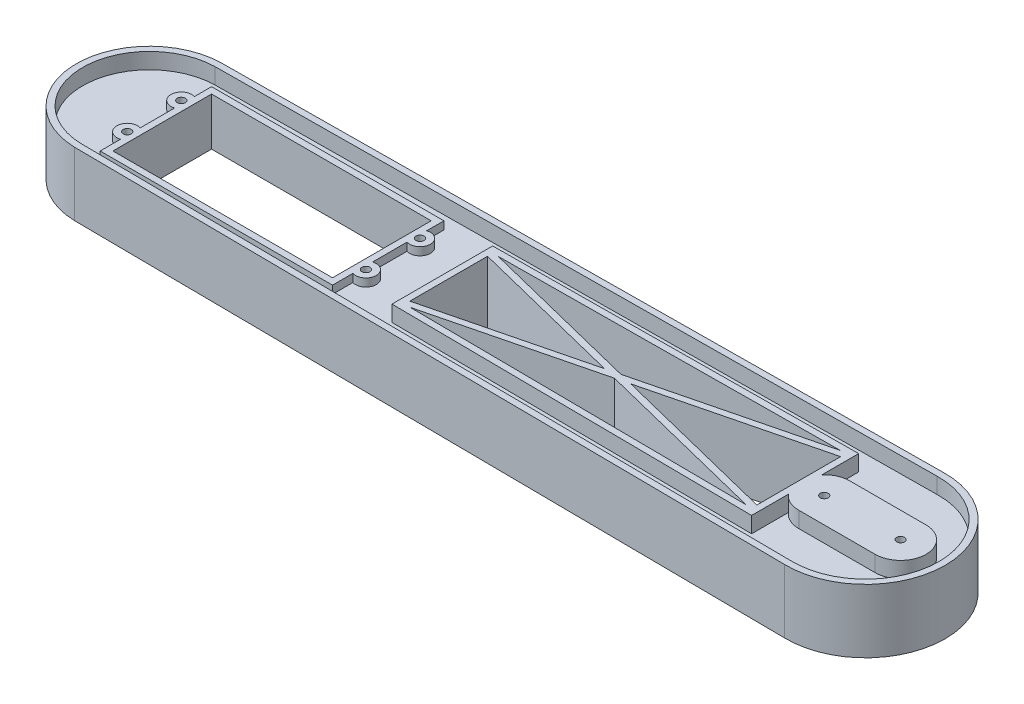
SolidWorks part; units mm, degrees
material "PET"
ref_plane "Front Plane" through (0, 0, 0) normal (0, 0, 1) x (1, 0, 0)
ref_plane "Top Plane" through (0, 0, 0) normal (0, 1, 0) x (1, 0, 0)
ref_plane "Right Plane" through (0, 0, 0) normal (1, 0, 0) x (0, 0, -1)
sketch "Sketch1" plane through (0, 0, 0) normal (0, 1, 0) x (1, 0, 0)
  line L0 (-0.4444, 19.9951) -> (0, 0) construction
  line L1 (-0.4444, 19.9951) -> (224.4444, 24.9938)
  line L2 (-55, 0) -> (55, 0) construction
  line L3 (-0.4444, -19.9951) -> (224.4444, -24.9938)
  line L4 (0, 0) -> (4, 0) construction
  line L5 (4, 0) -> (4, 15.5)
  line L6 (4, 15.5) -> (4, 0)
  line L7 (4, 15.5) -> (4, -15.5)
  line L8 (4, 15.5) -> (73, 15.5)
  line L9 (73, 15.5) -> (73, -15.5)
  line L10 (73, -15.5) -> (4, -15.5)
  line L11 (4, 15.5) -> (4, 9)
  line L12 (4, 9) -> (1, 9) construction
  line L13 (4, 0) -> (94, 0) construction
  line L14 (-0.2222, 9.9975) -> (224.6667, 14.9963) construction
  line L15 (-0.2222, -9.9975) -> (224.6667, -14.9963) construction
  line L16 (94, 0) -> (94, 12.0919)
  line L17 (94, 12.0919) -> (94, -12.0919)
  line L18 (94, 0) -> (204, 0) construction
  line L19 (204, 0) -> (204, 14.5369)
  line L20 (204, 14.5369) -> (204, -14.5369)
  line L21 (94, 12.0919) -> (204, 14.5369)
  line L22 (94, -12.0919) -> (204, -14.5369)
  line L23 (204, 0) -> (212, 0) construction
  line L24 (212, 0) -> (236, 0) construction
  arc A0 (224.4444, -24.9938) -> (224.4444, 24.9938) centre (225, 0) ccw
  arc A1 (-0.4444, 19.9951) -> (-0.4444, -19.9951) centre (0, 0) ccw
  circle A2 centre (1, 9) radius 1.25
  circle A3 centre (76, 9) radius 1.25
  circle A4 centre (76, -8) radius 1.25
  circle A5 centre (1, -8) radius 1.25
  arc A6 (224.6667, -14.9963) -> (224.6667, 14.9963) centre (225, 0) ccw construction
  arc A7 (-0.2222, 9.9975) -> (-0.2222, -9.9975) centre (0, 0) ccw construction
  circle A8 centre (212, 0) radius 1.25
  circle A9 centre (236, 0) radius 1.25
  dimension "D2" = 50
  dimension "D3" = 40
  dimension "D10" = 2.5
  dimension "D18" = 2.5
  dimension "D19" = 2.5
  dimension "D1" = 225
  dimension "D4" = 4
  dimension "D5" = 15.5
  dimension "D6" = 31
  dimension "D7" = 69
  dimension "D8" = 6.5
  dimension "D9" = 3
  dimension "D13" = 90
  dimension "D15" = 110
  dimension "D16" = 24
  dimension "D17" = 8
  dimension "D14" = 10
  dimension "D11" = 2
  dimension "D12" = 2
extrude "Boss-Extrude2" add sketch "Sketch1" along normal blind 10 contours L1 A1 L3 A0 A9 A8 A5 A4 A3 A2 L9 L10 L7 L5 L8 L22 L17 L16 L21 L19 L20
sketch "Sketch3" plane through (0, 10, 0) normal (0, 1, 0) x (1, 0, 0)
  line L1 (-0.5111, -22.9943) -> (224.4444, -24.9938)
  line L2 (224.4444, 24.9938) -> (-0.5111, 22.9943)
  arc A1 (-0.5111, 22.9943) -> (-0.5111, -22.9943) centre (0, 0) ccw
  arc A2 (224.4444, -24.9938) -> (224.4444, 24.9938) centre (225, 0) ccw construction
  arc A3 (224.4444, -24.9938) -> (224.4444, 24.9938) centre (225, 0) ccw
  dimension "D1" = 224.9556
  dimension "D2" = 224.9556
sketch "Sketch4" plane through (0, 10, 0) normal (0, 1, 0) x (1, 0, 0)
  line L0 (73, -15.5) -> (4, -15.5) construction
  line L1 (73, 15.5) -> (73, -15.5) construction
  line L2 (4, 15.5) -> (73, 15.5) construction
  line L3 (4, 15.5) -> (4, -15.5) construction
  line L4 (73, -15.5) -> (4, -15.5)
  line L5 (73, 15.5) -> (73, -15.5)
  line L6 (4, 15.5) -> (73, 15.5)
  line L7 (4, 15.5) -> (4, -15.5)
  line L11 (204, -14.5369) -> (204, 14.5369) construction
  line L12 (204, -14.8117) -> (204, 14.8117)
  line L14 (94, 13.834) -> (94, -13.834)
  line L16 (94, 12.0919) -> (94, -12.0919) construction
  line L17 (224.4444, 24.9938) -> (-0.5111, 22.9943) construction
  line L18 (94, 13.834) -> (204, 14.8117)
  line L19 (94, -13.834) -> (204, -14.8117)
  line L21 (-0.5111, -22.9943) -> (224.4444, -24.9938) construction
  circle A0 centre (1, 9) radius 1.25 construction
  circle A1 centre (1, -8) radius 1.25 construction
  circle A2 centre (1, 9) radius 1.25
  circle A3 centre (1, -8) radius 1.25
  circle A4 centre (76, 9) radius 1.25 construction
  circle A5 centre (76, -8) radius 1.25 construction
  circle A6 centre (76, 9) radius 1.25
  circle A7 centre (76, -8) radius 1.25
  circle A8 centre (212, 0) radius 1.25 construction
  circle A9 centre (212, 0) radius 1.25
  circle A10 centre (236, 0) radius 1.25 construction
  circle A11 centre (236, 0) radius 1.25
  dimension "D1" = 10
  dimension "D2" = 10
extrude "Boss-Extrude3" add sketch "Sketch3" against normal blind 10
extrude "Cut-Extrude1" cut sketch "Sketch4" against normal blind 10
sketch "Sketch5" plane through (0, 0, 0) normal (0, -1, 0) x (1, 0, 0)
  line L0 (4, 15.5) -> (73, 15.5) construction
  line L1 (4, -15.5) -> (4, 15.5) construction
  line L2 (-0.5111, -22.9943) -> (224.4444, -24.9938)
  line L3 (224.4444, 24.9938) -> (-0.5111, 22.9943)
  line L4 (-0.5111, -22.9943) -> (224.4444, -24.9938)
  line L5 (224.4444, 24.9938) -> (-0.5111, 22.9943)
  line L6 (73, 15.5) -> (73, -15.5) construction
  line L7 (73, -15.5) -> (4, -15.5) construction
  line L8 (73, -15.5) -> (4, -15.5)
  line L9 (73, 15.5) -> (73, -15.5)
  line L10 (4, -15.5) -> (4, 15.5)
  line L11 (4, 15.5) -> (73, 15.5)
  line L12 (204, -14.8117) -> (94, -13.834) construction
  line L13 (204, 14.8117) -> (204, -14.8117) construction
  line L14 (94, 13.834) -> (204, 14.8117) construction
  line L15 (94, -13.834) -> (94, 13.834) construction
  line L16 (204, -14.8117) -> (94, -13.834)
  line L17 (204, 14.8117) -> (204, -14.8117)
  line L18 (94, 13.834) -> (204, 14.8117)
  line L19 (94, -13.834) -> (94, 13.834)
  circle A0 centre (1, 8) radius 1.25 construction
  circle A1 centre (1, 8) radius 1.25
  circle A2 centre (1, -9) radius 1.25 construction
  circle A3 centre (1, -9) radius 1.25
  circle A4 centre (76, 8) radius 1.25 construction
  circle A5 centre (76, 8) radius 1.25
  circle A6 centre (76, -9) radius 1.25 construction
  circle A7 centre (76, -9) radius 1.25
  circle A8 centre (212, 0) radius 1.25 construction
  circle A9 centre (212, 0) radius 1.25
  circle A10 centre (236, 0) radius 1.25 construction
  circle A11 centre (236, 0) radius 1.25
  arc A14 (224.4444, -24.9938) -> (224.4444, 24.9938) centre (225, 0) ccw
  arc A15 (-0.5111, 22.9943) -> (-0.5111, -22.9943) centre (0, 0) ccw
  arc A16 (224.4444, -24.9938) -> (224.4444, 24.9938) centre (225, 0) ccw
  arc A17 (-0.5111, 22.9943) -> (-0.5111, -22.9943) centre (0, 0) ccw
  dimension "D1" = 0
extrude "Boss-Extrude4" add sketch "Sketch5" along normal blind 5
sketch "Sketch6" plane through (0, -5, 0) normal (0, -1, 0) x (1, 0, 0)
  line L0 (2, 4.9077) -> (2, -5.9077)
  line L1 (2, -12.0923) -> (2, -17.5)
  line L2 (75, -5.9077) -> (75, 4.9077)
  line L3 (75, 11.0923) -> (75, 17.5)
  line L4 (-0.4797, -20.9945) -> (224.4758, -22.994)
  line L5 (224.4758, 22.994) -> (-0.4797, 20.9945)
  line L6 (-0.4797, -20.9945) -> (224.4758, -22.994)
  line L7 (224.4758, 22.994) -> (-0.4797, 20.9945)
  line L14 (75, 17.5) -> (2, 17.5)
  line L15 (75, -17.5) -> (75, 17.5)
  line L16 (2, -17.5) -> (75, -17.5)
  line L17 (2, 17.5) -> (2, -17.5)
  line L18 (75, 17.5) -> (2, 17.5)
  line L19 (75, -17.5) -> (75, -12.0923)
  line L20 (2, -17.5) -> (75, -17.5)
  line L21 (2, 17.5) -> (2, 11.0923)
  line L24 (92, 15.8163) -> (92, -15.8163)
  line L25 (92, -15.8163) -> (206, -16.8296)
  line L26 (206, -16.8296) -> (206, 16.8296)
  line L27 (206, 16.8296) -> (92, 15.8163)
  line L28 (92, 15.8163) -> (92, -15.8163)
  line L29 (92, -15.8163) -> (206, -16.8296)
  line L30 (206, -16.8296) -> (206, 16.8296)
  line L31 (206, 16.8296) -> (92, 15.8163)
  circle A2 centre (76, -9) radius 3.25
  arc A3 (75, -12.0923) -> (75, -5.9077) centre (76, -9) ccw
  arc A4 (-0.4797, 20.9945) -> (-0.4797, -20.9945) centre (0, 0) ccw
  arc A5 (224.4758, -22.994) -> (224.4758, 22.994) centre (225, 0) ccw
  arc A6 (-0.4797, 20.9945) -> (-0.4797, -20.9945) centre (0, 0) ccw
  arc A7 (224.4758, -22.994) -> (224.4758, 22.994) centre (225, 0) ccw
  circle A9 centre (212, 0) radius 3.25
  circle A10 centre (212, 0) radius 3.25
  circle A12 centre (236, 0) radius 3.25
  circle A13 centre (236, 0) radius 3.25
  circle A19 centre (1, 8) radius 3.25
  arc A20 (2, 11.0923) -> (2, 4.9077) centre (1, 8) ccw
  circle A22 centre (1, -9) radius 3.25
  arc A23 (2, -5.9077) -> (2, -12.0923) centre (1, -9) ccw
  circle A25 centre (76, 8) radius 3.25
  arc A26 (75, 4.9077) -> (75, 11.0923) centre (76, 8) ccw
  dimension "D1" = 2
  dimension "D2" = 2
  dimension "D3" = 2
  dimension "D4" = 2
  dimension "D5" = 2
  dimension "D6" = 2
  dimension "D7" = 2
  dimension "D8" = 2
  dimension "D9" = 2
extrude "Cut-Extrude2" cut sketch "Sketch6" against normal blind 5
sketch "Sketch7" plane through (0, 10, 0) normal (0, 1, 0) x (1, 0, 0)
  line L2 (224.4444, 24.9938) -> (-0.5111, 22.9943)
  line L3 (-0.5111, -22.9943) -> (224.4444, -24.9938)
  line L4 (73, 15.5) -> (4, 15.5)
  line L5 (4, 15.5) -> (4, -15.5)
  line L6 (4, -15.5) -> (73, -15.5)
  line L7 (73, -15.5) -> (73, 15.5)
  line L8 (73, 15.5) -> (4, 15.5)
  line L9 (4, 15.5) -> (4, -15.5)
  line L10 (4, -15.5) -> (73, -15.5)
  line L11 (73, -15.5) -> (73, 15.5)
  line L12 (224.4444, 24.9938) -> (-0.5111, 22.9943)
  line L13 (-0.5111, -22.9943) -> (224.4444, -24.9938)
  line L16 (94, 13.834) -> (94, -13.834)
  line L17 (204, 14.8117) -> (94, 13.834)
  line L18 (204, -14.8117) -> (204, 14.8117)
  line L19 (94, -13.834) -> (204, -14.8117)
  line L20 (94, 13.834) -> (94, -13.834)
  line L21 (204, 14.8117) -> (94, 13.834)
  line L22 (204, -14.8117) -> (204, 14.8117)
  line L23 (94, -13.834) -> (204, -14.8117)
  circle A1 centre (212, 0) radius 1.25
  circle A2 centre (212, 0) radius 1.25
  circle A3 centre (76, 9) radius 1.25
  circle A4 centre (76, 9) radius 1.25
  circle A5 centre (76, -8) radius 1.25
  circle A6 centre (76, -8) radius 1.25
  circle A7 centre (1, 9) radius 1.25
  circle A8 centre (1, 9) radius 1.25
  circle A9 centre (1, -8) radius 1.25
  circle A10 centre (1, -8) radius 1.25
  circle A11 centre (236, 0) radius 1.25
  circle A12 centre (236, 0) radius 1.25
  arc A14 (224.4444, -24.9938) -> (224.4444, 24.9938) centre (225, 0) ccw
  arc A15 (-0.5111, 22.9943) -> (-0.5111, -22.9943) centre (0, 0) ccw
  arc A16 (224.4444, -24.9938) -> (224.4444, 24.9938) centre (225, 0) ccw
  arc A17 (-0.5111, 22.9943) -> (-0.5111, -22.9943) centre (0, 0) ccw
  dimension "D1" = 0
  dimension "D2" = 0
  dimension "D3" = 0
  dimension "D4" = 0
  dimension "D5" = 0
  dimension "D6" = 0
  dimension "D7" = 0
  dimension "D8" = 0
  dimension "D9" = 0
extrude "Boss-Extrude5" add sketch "Sketch7" along normal blind 5
sketch "Sketch8" plane through (0, 15, 0) normal (0, 1, 0) x (1, 0, 0)
  line L2 (224.4758, 22.994) -> (-0.4797, 20.9945)
  line L3 (-0.4797, -20.9945) -> (224.4758, -22.994)
  line L4 (224.4758, 22.994) -> (-0.4797, 20.9945)
  line L5 (-0.4797, -20.9945) -> (224.4758, -22.994)
  line L8 (206, 16.8296) -> (92, 15.8163)
  line L9 (206, -16.8296) -> (206, 16.8296)
  line L10 (92, -15.8163) -> (206, -16.8296)
  line L11 (92, 15.8163) -> (92, -15.8163)
  line L12 (75, -4.9077) -> (75, 5.9077)
  line L13 (75, 12.0923) -> (75, 17.5)
  line L14 (75, 17.5) -> (2, 17.5)
  line L15 (2, 17.5) -> (2, 12.0923)
  line L16 (2, 5.9077) -> (2, -4.9077)
  line L17 (2, -11.0923) -> (2, -17.5)
  line L18 (2, -17.5) -> (75, -17.5)
  line L19 (75, -17.5) -> (75, -11.0923)
  line L20 (75, -4.9077) -> (75, 5.9077)
  line L21 (75, 12.0923) -> (75, 17.5)
  line L22 (75, 17.5) -> (2, 17.5)
  line L23 (2, 17.5) -> (2, 12.0923)
  line L24 (2, 5.9077) -> (2, -4.9077)
  line L25 (2, -11.0923) -> (2, -17.5)
  line L26 (2, -17.5) -> (75, -17.5)
  line L27 (75, -17.5) -> (75, -11.0923)
  line L28 (206, 16.8296) -> (92, 15.8163)
  line L29 (206, -16.8296) -> (206, 16.8296)
  line L30 (92, -15.8163) -> (206, -16.8296)
  line L31 (92, 15.8163) -> (92, -15.8163)
  circle A1 centre (212, 0) radius 3.25
  circle A2 centre (212, 0) radius 3.25
  circle A3 centre (236, 0) radius 3.25
  arc A4 (224.4758, -22.994) -> (224.4758, 22.994) centre (225, 0) ccw
  arc A5 (-0.4797, 20.9945) -> (-0.4797, -20.9945) centre (0, 0) ccw
  arc A6 (224.4758, -22.994) -> (224.4758, 22.994) centre (225, 0) ccw
  arc A7 (-0.4797, 20.9945) -> (-0.4797, -20.9945) centre (0, 0) ccw
  circle A8 centre (236, 0) radius 3.25
  arc A10 (75, 5.9077) -> (75, 12.0923) centre (76, 9) ccw
  arc A11 (2, 12.0923) -> (2, 5.9077) centre (1, 9) ccw
  arc A12 (2, -4.9077) -> (2, -11.0923) centre (1, -8) ccw
  arc A13 (75, -11.0923) -> (75, -4.9077) centre (76, -8) ccw
  arc A14 (75, 5.9077) -> (75, 12.0923) centre (76, 9) ccw
  arc A15 (2, 12.0923) -> (2, 5.9077) centre (1, 9) ccw
  arc A16 (2, -4.9077) -> (2, -11.0923) centre (1, -8) ccw
  arc A17 (75, -11.0923) -> (75, -4.9077) centre (76, -8) ccw
  dimension "D1" = 0
  dimension "D2" = 0
  dimension "D3" = 0
  dimension "D4" = 0
  dimension "D5" = 0
extrude "Cut-Extrude3" cut sketch "Sketch8" against normal blind 5
sketch "Sketch9" plane through (0, -5, 0) normal (0, -1, 0) x (1, 0, 0)
  line L8 (2, 17.5) -> (2, 11.0923)
  line L9 (2, 4.9077) -> (2, -5.9077)
  line L10 (2, -12.0923) -> (2, -17.5)
  line L11 (2, -17.5) -> (75, -17.5)
  line L12 (75, -17.5) -> (75, -12.0923)
  line L13 (75, -5.9077) -> (75, 4.9077)
  line L14 (75, 11.0923) -> (75, 17.5)
  line L15 (75, 17.5) -> (2, 17.5)
  line L16 (2, 17.5) -> (2, 11.0923)
  line L17 (2, 4.9077) -> (2, -5.9077)
  line L18 (2, -12.0923) -> (2, -17.5)
  line L19 (2, -17.5) -> (75, -17.5)
  line L20 (75, -17.5) -> (75, -12.0923)
  line L21 (75, -5.9077) -> (75, 4.9077)
  line L22 (75, 11.0923) -> (75, 17.5)
  line L23 (75, 17.5) -> (2, 17.5)
  arc A4 (2, 11.0923) -> (2, 4.9077) centre (1, 8) ccw
  arc A5 (2, -5.9077) -> (2, -12.0923) centre (1, -9) ccw
  arc A6 (75, -12.0923) -> (75, -5.9077) centre (76, -9) ccw
  arc A7 (75, 4.9077) -> (75, 11.0923) centre (76, 8) ccw
  arc A8 (2, 11.0923) -> (2, 4.9077) centre (1, 8) ccw
  arc A9 (2, -5.9077) -> (2, -12.0923) centre (1, -9) ccw
  arc A10 (75, -12.0923) -> (75, -5.9077) centre (76, -9) ccw
  arc A11 (75, 4.9077) -> (75, 11.0923) centre (76, 8) ccw
  dimension "D1" = 0
extrude "Cut-Extrude4" cut sketch "Sketch9" against normal blind 2.5
sketch "Sketch10" plane through (0, 15, 0) normal (0, 1, 0) x (1, 0, 0)
  line L8 (75, -4.9077) -> (75, 5.9077)
  line L9 (75, 12.0923) -> (75, 17.5)
  line L10 (75, 17.5) -> (2, 17.5)
  line L11 (2, 17.5) -> (2, 12.0923)
  line L12 (2, 5.9077) -> (2, -4.9077)
  line L13 (2, -11.0923) -> (2, -17.5)
  line L14 (2, -17.5) -> (75, -17.5)
  line L15 (75, -17.5) -> (75, -11.0923)
  line L16 (75, -4.9077) -> (75, 5.9077)
  line L17 (75, 12.0923) -> (75, 17.5)
  line L18 (75, 17.5) -> (2, 17.5)
  line L19 (2, 17.5) -> (2, 12.0923)
  line L20 (2, 5.9077) -> (2, -4.9077)
  line L21 (2, -11.0923) -> (2, -17.5)
  line L22 (2, -17.5) -> (75, -17.5)
  line L23 (75, -17.5) -> (75, -11.0923)
  arc A4 (75, 5.9077) -> (75, 12.0923) centre (76, 9) ccw
  arc A5 (2, 12.0923) -> (2, 5.9077) centre (1, 9) ccw
  arc A6 (2, -4.9077) -> (2, -11.0923) centre (1, -8) ccw
  arc A7 (75, -11.0923) -> (75, -4.9077) centre (76, -8) ccw
  arc A8 (75, 5.9077) -> (75, 12.0923) centre (76, 9) ccw
  arc A9 (2, 12.0923) -> (2, 5.9077) centre (1, 9) ccw
  arc A10 (2, -4.9077) -> (2, -11.0923) centre (1, -8) ccw
  arc A11 (75, -11.0923) -> (75, -4.9077) centre (76, -8) ccw
  dimension "D1" = 0
extrude "Cut-Extrude5" cut sketch "Sketch10" against normal blind 2.5
sketch "Sketch13" plane through (0, 15, 0) normal (0, 1, 0) x (1, 0, 0)
  line L0 (212, 0) -> (236, 0) construction
  line L4 (212, 8) -> (236, 8)
  line L5 (212, -8) -> (236, -8)
  line L6 (204, -14.8117) -> (204, 14.8117) construction
  arc A6 (212, 8) -> (212, -8) centre (212, 0) ccw
  arc A7 (236, -8) -> (236, 8) centre (236, 0) ccw
  circle A8 centre (236, 0) radius 1.25 construction
  circle A9 centre (212, 0) radius 1.25 construction
  circle A10 centre (236, 0) radius 1.25
  circle A11 centre (212, 0) radius 1.25
  point P4 (224, 0)
extrude "Boss-Extrude6" add sketch "Sketch13" against normal blind 20
sketch "Sketch16" plane through (0, 15, 0) normal (0, 1, 0) x (1, 0, 0)
  line L0 (94, 12.2148) -> (142.9693, 0)
  line L1 (94, 13.834) -> (94, -13.834) construction
  line L2 (94, -13.834) -> (204, -14.8117) construction
  line L3 (95.7114, 13.8492) -> (147.1011, 1.0306)
  line L4 (204, 14.8117) -> (94, 13.834) construction
  line L5 (204, -14.8117) -> (204, 14.8117) construction
  line L6 (94, 12.2148) -> (95.7114, 13.8492) construction
  line L7 (202.2886, -14.7965) -> (204, -13.1621) construction
  line L8 (94, 12.2148) -> (94, 13.834)
  line L9 (94, 13.834) -> (95.7114, 13.8492)
  line L10 (202.2886, -14.7965) -> (204, -14.8117)
  line L11 (204, -14.8117) -> (204, -13.1621)
  line L12 (94, 0) -> (204, 0) construction
  line L13 (202.2886, 14.7965) -> (204, 14.8117)
  line L14 (94, -12.2148) -> (142.9693, 0)
  line L15 (94, -12.2148) -> (94, -13.834)
  line L16 (94, -13.834) -> (95.7114, -13.8492)
  line L17 (95.7114, -13.8492) -> (147.1011, -1.0306)
  line L18 (204, 14.8117) -> (204, 13.1621)
  line L19 (151.233, 0) -> (204, 13.1621)
  line L20 (151.233, 0) -> (204, -13.1621)
  line L21 (147.1011, 1.0306) -> (202.2886, 14.7965)
  line L22 (147.1011, -1.0306) -> (202.2886, -14.7965)
  dimension "D1" = 2
  dimension "D2" = 108.2886
extrude "Boss-Extrude7" add sketch "Sketch16" against normal blind 20
